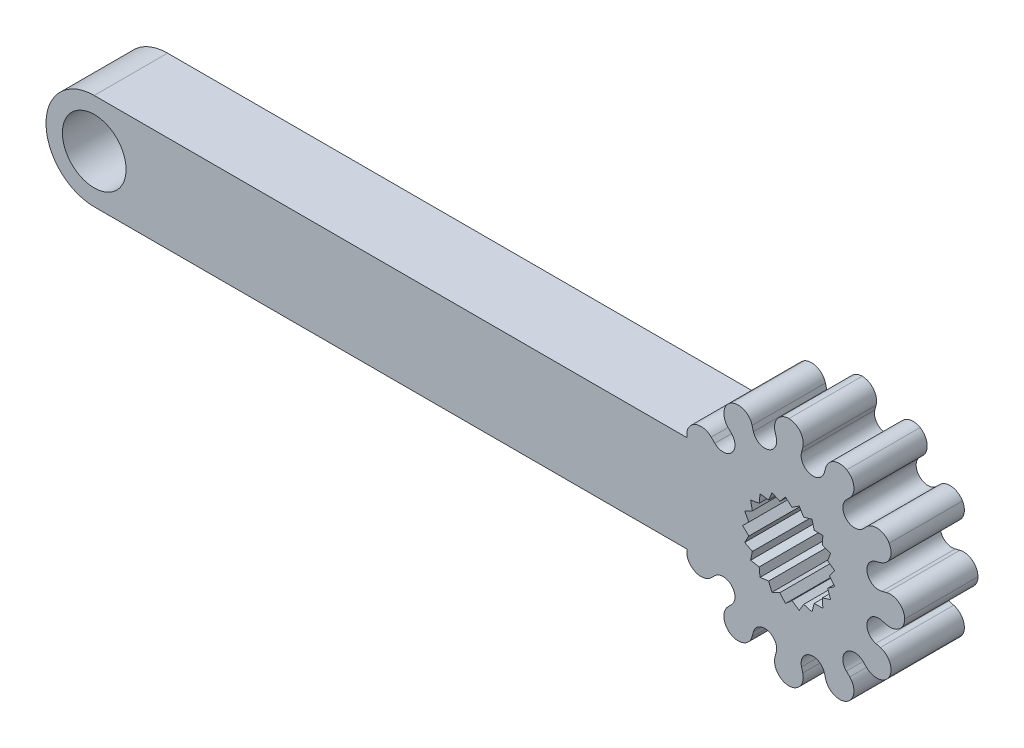
SolidWorks part; units mm, degrees
material "Anycubic PLA V3.0"
ref_plane "Front Plane" through (0, 0, 0) normal (0, 0, 1) x (1, 0, 0)
ref_plane "Top Plane" through (0, 0, 0) normal (0, 1, 0) x (1, 0, 0)
ref_plane "Right Plane" through (0, 0, 0) normal (1, 0, 0) x (0, 0, -1)
sketch "Sketch1" plane through (0, 0, 0) normal (0, 0, 1) x (1, 0, 0)
  line L0 (18, 0) -> (-18, 0) construction
  line L1 (-18, 2.5) -> (12.5456, 2.5)
  line L2 (-18, -2.5) -> (12.5456, -2.5)
  arc A0 (-18, 2.5) -> (-18, -2.5) centre (-18, 0) ccw
  circle A1 centre (-18, 0) radius 1.65
  arc A2 (12.5456, -2.5) -> (12.5456, 2.5) centre (18, 0) ccw
  point P4 (0, 0)
  dimension "D2" = 12
  dimension "D3" = 3.3
  dimension "D4" = 5
  dimension "D1" = 36
extrude "Boss-Extrude1" add sketch "Sketch1" along normal blind 3.8
sketch "Sketch2" plane through (0, 0, 3.8) normal (0, 0, 1) x (1, 0, 0)
  line L0 (18, 6) -> (18, -6) construction
  line L1 (18, 0) -> (21, 5.1962) construction
  line L2 (18, 0) -> (19.2475, 4.6558) construction
  line L3 (18.72, 5.06) -> (18.6545, 4.81)
  line L4 (18.6545, 4.81) -> (19.8405, 4.5015) construction
  line L5 (19.9065, 4.7421) -> (19.8405, 4.5015)
  arc A0 (12.5456, -2.5) -> (12.5456, 2.5) centre (18, 0) ccw construction
  arc A1 (18, 6) -> (18.72, 5.06) centre (17.9945, 5.25) cw
  arc A2 (18.6545, 4.81) -> (19.8405, 4.5015) centre (19.2475, 4.6558) ccw
  arc A3 (21, 5.1962) -> (19.9065, 4.7421) centre (20.6298, 4.5439) ccw
  arc A6 (18, 6) -> (21, 5.1962) centre (18.963, 3.5938) cw
  dimension "D4" = 0.94
  dimension "D6" = 0.75
  dimension "D1" = 30
  dimension "D2" = 4.82
  dimension "D3" = 15
  dimension "D5" = 0.72
  dimension "D8" = 0.25
extrude "Cut-Extrude1" cut sketch "Sketch2" against normal through all
pattern_circular "CirPattern1" count 12 over 360 about axis through (18, 0, 0) along (0, 0, 1) of "Cut-Extrude1"
sketch "Sketch3" plane through (0, 0, 3.8) normal (0, 0, 1) x (1, 0, 0)
  line L0 (12.3194, 2.5) -> (-18, 2.5) construction
  line L1 (10.2871, 2.5) -> (16.2777, 2.5)
  line L2 (10.2871, 2.5) -> (10.2871, -2.5)
  line L3 (10.2871, -2.5) -> (16.2777, -2.5)
  line L4 (16.2777, 2.5) -> (16.2777, -2.5)
  line L5 (-18, -2.5) -> (12.3194, -2.5) construction
extrude "Boss-Extrude2" add sketch "Sketch3" against normal blind 3.8
sketch "Sketch4" plane through (0, 0, 3.8) normal (0, 0, 1) x (1, 0, 0)
  line L0 (18, 6) -> (18, -6) construction
  circle A0 centre (18, 0) radius 2.1
  point P7 (18, 0)
  dimension "D1" = 4.2
extrude "Cut-Extrude2" cut sketch "Sketch4" against normal through all
sketch "Sketch5" plane through (0, 0, 3.8) normal (0, 0, 1) x (1, 0, 0)
  line L0 (15.6, 0) -> (20.4, 0) construction
  line L1 (18, 0) -> (20.4, 0) construction
  line L2 (18, 0) -> (20.2934, 0.7074) construction
  line L3 (18, 0) -> (20.3732, 0.3577) construction
  line L4 (20.0067, 0.619) -> (20.3732, 0.3577)
  line L5 (20.1, 0) -> (20.3732, 0.3577)
  line L6 (20.1, 0) -> (20.3732, -0.3577)
  line L7 (20.0067, -0.619) -> (20.3732, -0.3577)
  line L8 (20.0067, -0.619) -> (20.1623, -1.0413)
  line L9 (19.7351, -1.183) -> (20.1623, -1.0413)
  line L10 (19.7351, -1.183) -> (19.7593, -1.6324)
  line L11 (19.3093, -1.6418) -> (19.7593, -1.6324)
  line L12 (19.3093, -1.6419) -> (19.2, -2.0785)
  line L13 (18.7672, -1.9548) -> (19.2, -2.0785)
  line L14 (18.7672, -1.9548) -> (18.534, -2.3398)
  line L15 (18.1569, -2.0941) -> (18.534, -2.3398)
  line L16 (18.1569, -2.0941) -> (17.8206, -2.3933)
  line L17 (17.5327, -2.0473) -> (17.8206, -2.3933)
  line L18 (17.5327, -2.0473) -> (17.1232, -2.2341)
  line L19 (16.95, -1.8187) -> (17.1232, -2.2341)
  line L20 (16.95, -1.8186) -> (16.5036, -1.8764)
  line L21 (16.4606, -1.4284) -> (16.5036, -1.8764)
  line L22 (16.4606, -1.4283) -> (16.017, -1.352)
  line L23 (16.108, -0.9112) -> (16.017, -1.352)
  line L24 (16.108, -0.9111) -> (15.7066, -0.7074)
  line L25 (15.9235, -0.313) -> (15.7066, -0.7074)
  line L26 (15.9235, -0.313) -> (15.6, 0)
  line L27 (15.9235, 0.313) -> (15.6, 0)
  line L28 (15.9235, 0.313) -> (15.7066, 0.7074)
  line L29 (16.108, 0.9112) -> (15.7066, 0.7074)
  line L30 (16.108, 0.9112) -> (16.017, 1.352)
  line L31 (16.4606, 1.4284) -> (16.017, 1.352)
  line L32 (16.4606, 1.4284) -> (16.5036, 1.8764)
  line L33 (16.95, 1.8187) -> (16.5036, 1.8764)
  line L34 (16.95, 1.8187) -> (17.1232, 2.2341)
  line L35 (17.5327, 2.0473) -> (17.1232, 2.2341)
  line L36 (17.5327, 2.0474) -> (17.8207, 2.3933)
  line L37 (18.1569, 2.0941) -> (17.8207, 2.3933)
  line L38 (18.157, 2.0941) -> (18.5341, 2.3398)
  line L39 (18.7672, 1.9548) -> (18.5341, 2.3398)
  line L40 (18.7672, 1.9548) -> (19.2, 2.0785)
  line L41 (19.3093, 1.6418) -> (19.2, 2.0785)
  line L42 (19.3094, 1.6418) -> (19.7593, 1.6324)
  line L43 (19.7351, 1.183) -> (19.7593, 1.6324)
  line L44 (19.7351, 1.1829) -> (20.1623, 1.0413)
  line L45 (20.0067, 0.619) -> (20.1623, 1.0413)
  circle A0 centre (18, 0) radius 2.4 construction
  circle A1 centre (18, 0) radius 2.1
  arc A3 (20.0067, 0.619) -> (20.1, 0) centre (18, 0) cw
  circle A5 centre (18, 0) radius 2.1 construction
  arc A6 (20.1, 0) -> (20.0067, -0.619) centre (18, 0) cw
  arc A7 (20.0067, -0.619) -> (19.7351, -1.183) centre (18, 0) cw
  arc A8 (19.7351, -1.183) -> (19.3093, -1.6418) centre (18, 0) cw
  arc A9 (19.3093, -1.6419) -> (18.7672, -1.9548) centre (18, 0) cw
  arc A10 (18.7672, -1.9548) -> (18.1569, -2.0941) centre (18, 0) cw
  arc A11 (18.1569, -2.0941) -> (17.5327, -2.0473) centre (18, 0) cw
  arc A12 (17.5327, -2.0473) -> (16.95, -1.8187) centre (18, 0) cw
  arc A13 (16.95, -1.8186) -> (16.4606, -1.4284) centre (18, 0) cw
  arc A14 (16.4606, -1.4283) -> (16.108, -0.9112) centre (18, 0) cw
  arc A15 (16.108, -0.9111) -> (15.9235, -0.313) centre (18, 0) cw
  arc A16 (15.9235, -0.313) -> (15.9235, 0.313) centre (18, 0) cw
  arc A17 (15.9235, 0.313) -> (16.108, 0.9112) centre (18, 0) cw
  arc A18 (16.108, 0.9112) -> (16.4606, 1.4284) centre (18, 0) cw
  arc A19 (16.4606, 1.4284) -> (16.95, 1.8187) centre (18, 0) cw
  arc A20 (16.95, 1.8187) -> (17.5327, 2.0473) centre (18, 0) cw
  arc A21 (17.5327, 2.0474) -> (18.1569, 2.0941) centre (18, 0) cw
  arc A22 (18.157, 2.0941) -> (18.7672, 1.9548) centre (18, 0) cw
  arc A23 (18.7672, 1.9548) -> (19.3093, 1.6418) centre (18, 0) cw
  arc A24 (19.3094, 1.6418) -> (19.7351, 1.183) centre (18, 0) cw
  arc A25 (19.7351, 1.1829) -> (20.0067, 0.619) centre (18, 0) cw
  dimension "D1" = 4.8
  dimension "D2" = 8.571
  dimension "D3" = 8.571
  dimension "D4" = 21
extrude "Cut-Extrude3" cut sketch "Sketch5" against normal blind 10 contours A1 L37 L36 | A1 L11 L10 | A1 L13 L12 | A1 L15 L14 | A1 L17 L16 | A1 L19 L18 | A1 | A1 L21 L20 | A1 L23 L22 | A1 L25 L24 | A1 L27 L26 | A1 L29 L28 | L30 L31 A18 | L32 L33 A19 | L35 L34 A20 | L38 L39 A22 | L40 L41 A23 | L42 L43 A24 | L45 L44 A25 | L4 L5 A3 | L6 L7 A6 | L8 L9 A7
